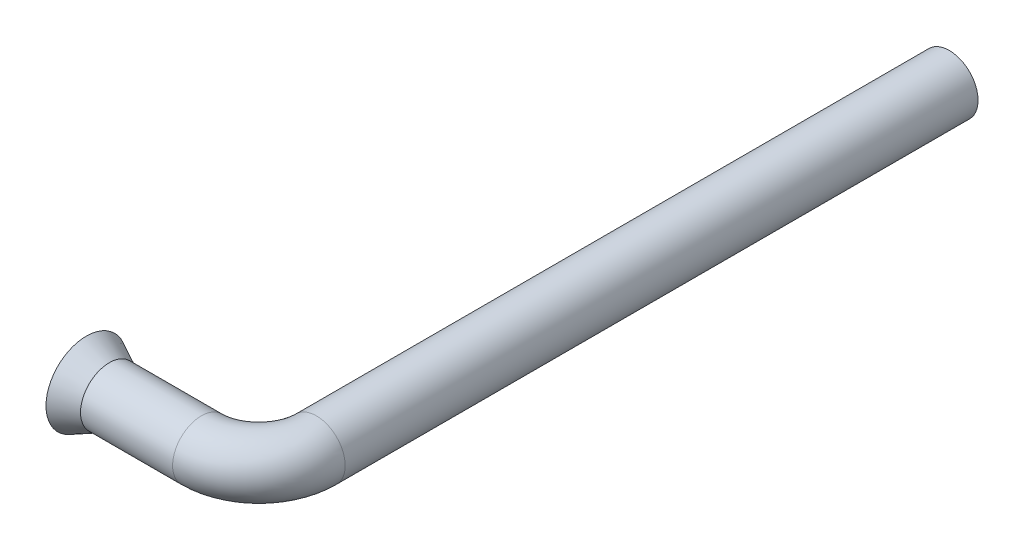
SolidWorks part; units mm, degrees
ref_plane "Спереди" through (0, 0, 0) normal (0, 0, 1) x (1, 0, 0)
ref_plane "Сверху" through (0, 0, 0) normal (0, 1, 0) x (1, 0, 0)
ref_plane "Справа" through (0, 0, 0) normal (1, 0, 0) x (0, 0, -1)
sketch "Эскиз1" plane through (0, 0, 0) normal (0, 1, 0) x (1, 0, 0)
  line L0 (0, 0) -> (20, 0)
  line L1 (30, 10) -> (30, 120)
  arc A0 (20, 0) -> (30, 10) centre (20, 10) ccw
  dimension "D1" = 10
sketch "Эскиз2" plane through (0, 0, 0) normal (1, 0, 0) x (0, 0, -1)
  circle A0 centre (0, 0) radius 5
  circle A1 centre (0, 0) radius 4
  dimension "D1" = 10
  dimension "D2" = 8
sweep "По траектории1" add profiles "Эскиз2" path "Эскиз1"
sketch "Эскиз3" plane through (0, 0, 0) normal (0, 0, 1) x (1, 0, 0)
  line L0 (0, 7) -> (0, 4)
  line L1 (0, 7) -> (4, 5)
  line L2 (0, 4) -> (4, 4)
  line L3 (4, 4) -> (4, 5)
  line L4 (-3.4534, 0) -> (12.3837, 0) construction
revolve "Повернуть1" add sketch "Эскиз3" angle 360 about L4
